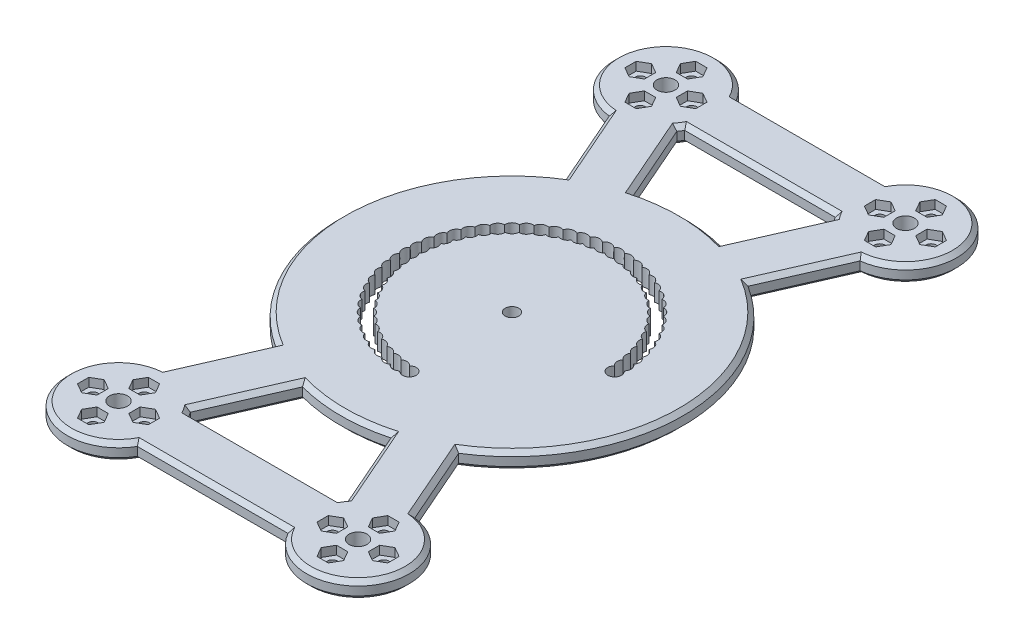
SolidWorks part; units mm, degrees
ref_plane "Front Plane" through (0, 0, 0) normal (0, 0, 1) x (1, 0, 0)
ref_plane "Top Plane" through (0, 0, 0) normal (0, 1, 0) x (1, 0, 0)
ref_plane "Right Plane" through (0, 0, 0) normal (1, 0, 0) x (0, 0, -1)
sketch "Sketch1" plane through (0, 0, 0) normal (0, 1, 0) x (1, 0, 0)
  line L1 (-50, -95) -> (50, -95)
  line L2 (-50, -95) -> (-50, 95)
  line L3 (-50, 95) -> (50, 95)
  line L4 (50, -95) -> (50, 95)
  line L5 (-50, -95) -> (50, 95) construction
  line L6 (-50, 95) -> (50, -95) construction
  point P0 (0, 0)
  dimension "D1" = 100
  dimension "D2" = 190
extrude "Boss-Extrude1" add sketch "Sketch1" along normal blind 5
sketch "Sketch2" plane through (0, 5, 0) normal (0, 1, 0) x (1, 0, 0)
  line L0 (0, 95) -> (0, -95) construction
  line L1 (50, 95) -> (-50, 95) construction
  line L2 (-50, -95) -> (50, -95) construction
  line L3 (-50, 0) -> (50, 0) construction
  line L4 (-50, 95) -> (-50, -95) construction
  line L5 (50, -95) -> (50, 95) construction
  line L6 (0, 0) -> (50, 0) construction
  line L7 (0, 0) -> (30, 0) construction
  circle A0 centre (0, 0) radius 2
  arc A1 (30, 0) -> (0, 30) centre (0, 0) ccw construction
  arc A31 (28.5755, 1.4038) -> (31.2801, 1.5367) centre (30, 0) ccw
  arc A33 (31.2801, 1.5367) -> (30.9788, 4.5953) centre (29.8555, 2.9405) ccw
  arc A34 (30.9788, 4.5953) -> (30.3792, 7.6096) centre (29.4236, 5.8527) ccw
  arc A35 (30.3792, 7.6096) -> (29.4871, 10.5506) centre (28.7082, 8.7085) ccw
  arc A36 (29.4871, 10.5506) -> (28.311, 13.3901) centre (27.7164, 11.4805) ccw
  arc A37 (28.311, 13.3901) -> (26.8622, 16.1006) centre (26.4576, 14.1419) ccw
  arc A38 (26.8622, 16.1006) -> (25.1547, 18.656) centre (24.9441, 16.6671) ccw
  arc A39 (25.1547, 18.656) -> (23.205, 21.0317) centre (23.1903, 19.0318) ccw
  arc A40 (23.205, 21.0317) -> (21.0317, 23.205) centre (21.2132, 21.2132) ccw
  arc A41 (21.0317, 23.205) -> (18.656, 25.1547) centre (19.0318, 23.1903) ccw
  arc A42 (18.656, 25.1547) -> (16.1006, 26.8622) centre (16.6671, 24.9441) ccw
  arc A43 (16.1006, 26.8622) -> (13.3901, 28.311) centre (14.1419, 26.4576) ccw
  arc A44 (13.3901, 28.311) -> (10.5506, 29.4871) centre (11.4805, 27.7164) ccw
  arc A45 (10.5506, 29.4871) -> (7.6096, 30.3792) centre (8.7085, 28.7082) ccw
  arc A46 (7.6096, 30.3792) -> (4.5953, 30.9788) centre (5.8527, 29.4236) ccw
  arc A47 (1.4038, 28.5755) -> (4.1979, 28.3003) centre (2.9405, 29.8555) ccw
  arc A48 (-1.4038, 28.5755) -> (1.4038, 28.5755) centre (0, 30) ccw
  arc A49 (-4.1979, 28.3003) -> (-1.4038, 28.5755) centre (-2.9405, 29.8555) ccw
  arc A50 (-6.9516, 27.7525) -> (-4.1979, 28.3003) centre (-5.8527, 29.4236) ccw
  arc A51 (-9.6384, 26.9375) -> (-6.9516, 27.7525) centre (-8.7085, 28.7082) ccw
  arc A52 (-12.2323, 25.8631) -> (-9.6384, 26.9375) centre (-11.4805, 27.7164) ccw
  arc A53 (-14.7084, 24.5396) -> (-12.2323, 25.8631) centre (-14.1419, 26.4576) ccw
  arc A54 (-17.0429, 22.9797) -> (-14.7084, 24.5396) centre (-16.6671, 24.9441) ccw
  arc A55 (-19.2133, 21.1986) -> (-17.0429, 22.9797) centre (-19.0318, 23.1903) ccw
  arc A56 (-21.1986, 19.2133) -> (-19.2133, 21.1986) centre (-21.2132, 21.2132) ccw
  arc A57 (-22.9797, 17.0429) -> (-21.1986, 19.2133) centre (-23.1903, 19.0318) ccw
  arc A58 (-24.5396, 14.7084) -> (-22.9797, 17.0429) centre (-24.9441, 16.6671) ccw
  arc A59 (-25.8631, 12.2323) -> (-24.5396, 14.7084) centre (-26.4576, 14.1419) ccw
  arc A60 (-26.9375, 9.6384) -> (-25.8631, 12.2323) centre (-27.7164, 11.4805) ccw
  arc A61 (-29.4871, 10.5506) -> (-30.3792, 7.6096) centre (-28.7082, 8.7085) ccw
  arc A62 (-28.3003, 4.1979) -> (-27.7525, 6.9516) centre (-29.4236, 5.8527) ccw
  arc A63 (-28.5755, 1.4038) -> (-28.3003, 4.1979) centre (-29.8555, 2.9405) ccw
  arc A64 (-28.5755, -1.4038) -> (-28.5755, 1.4038) centre (-30, 0) ccw
  arc A65 (-28.3003, -4.1979) -> (-28.5755, -1.4038) centre (-29.8555, -2.9405) ccw
  arc A66 (-27.7525, -6.9516) -> (-28.3003, -4.1979) centre (-29.4236, -5.8527) ccw
  arc A67 (-26.9375, -9.6384) -> (-27.7525, -6.9516) centre (-28.7082, -8.7085) ccw
  arc A68 (-25.8631, -12.2323) -> (-26.9375, -9.6384) centre (-27.7164, -11.4805) ccw
  arc A69 (-24.5396, -14.7084) -> (-25.8631, -12.2323) centre (-26.4576, -14.1419) ccw
  arc A70 (-22.9797, -17.0429) -> (-24.5396, -14.7084) centre (-24.9441, -16.6671) ccw
  arc A71 (-21.1986, -19.2133) -> (-22.9797, -17.0429) centre (-23.1903, -19.0318) ccw
  arc A72 (-19.2133, -21.1986) -> (-21.1986, -19.2133) centre (-21.2132, -21.2132) ccw
  arc A73 (-17.0429, -22.9797) -> (-19.2133, -21.1986) centre (-19.0318, -23.1903) ccw
  arc A74 (-14.7084, -24.5396) -> (-17.0429, -22.9797) centre (-16.6671, -24.9441) ccw
  arc A75 (-12.2323, -25.8631) -> (-14.7084, -24.5396) centre (-14.1419, -26.4576) ccw
  arc A76 (-9.6384, -26.9375) -> (-12.2323, -25.8631) centre (-11.4805, -27.7164) ccw
  arc A77 (-6.9516, -27.7525) -> (-9.6384, -26.9375) centre (-8.7085, -28.7082) ccw
  arc A78 (-4.1979, -28.3003) -> (-6.9516, -27.7525) centre (-5.8527, -29.4236) ccw
  arc A79 (-1.4038, -28.5755) -> (-4.1979, -28.3003) centre (-2.9405, -29.8555) ccw
  arc A80 (-1.5367, -31.2801) -> (-1.4038, -28.5755) centre (0, -30) ccw
  arc A81 (-4.5953, -30.9788) -> (-1.5367, -31.2801) centre (-2.9405, -29.8555) ccw
  arc A82 (-7.6096, -30.3792) -> (-4.5953, -30.9788) centre (-5.8527, -29.4236) ccw
  arc A83 (-10.5506, -29.4871) -> (-7.6096, -30.3792) centre (-8.7085, -28.7082) ccw
  arc A84 (-13.3901, -28.311) -> (-10.5506, -29.4871) centre (-11.4805, -27.7164) ccw
  arc A85 (-16.1006, -26.8622) -> (-13.3901, -28.311) centre (-14.1419, -26.4576) ccw
  arc A86 (-18.656, -25.1547) -> (-16.1006, -26.8622) centre (-16.6671, -24.9441) ccw
  arc A87 (-21.0317, -23.205) -> (-18.656, -25.1547) centre (-19.0318, -23.1903) ccw
  arc A88 (-23.205, -21.0317) -> (-21.0317, -23.205) centre (-21.2132, -21.2132) ccw
  arc A89 (-25.1547, -18.656) -> (-23.205, -21.0317) centre (-23.1903, -19.0318) ccw
  arc A90 (-26.8622, -16.1006) -> (-25.1547, -18.656) centre (-24.9441, -16.6671) ccw
  arc A91 (-28.311, -13.3901) -> (-26.8622, -16.1006) centre (-26.4576, -14.1419) ccw
  arc A92 (-29.4871, -10.5506) -> (-28.311, -13.3901) centre (-27.7164, -11.4805) ccw
  arc A93 (-30.3792, -7.6096) -> (-29.4871, -10.5506) centre (-28.7082, -8.7085) ccw
  arc A94 (-30.9788, -4.5953) -> (-30.3792, -7.6096) centre (-29.4236, -5.8527) ccw
  arc A95 (-31.2801, -1.5367) -> (-30.9788, -4.5953) centre (-29.8555, -2.9405) ccw
  arc A96 (-31.2801, 1.5367) -> (-31.2801, -1.5367) centre (-30, 0) ccw
  arc A97 (-30.9788, 4.5953) -> (-31.2801, 1.5367) centre (-29.8555, 2.9405) ccw
  arc A98 (-30.3792, 7.6096) -> (-30.9788, 4.5953) centre (-29.4236, 5.8527) ccw
  arc A99 (-27.7525, 6.9516) -> (-26.9375, 9.6384) centre (-28.7082, 8.7085) ccw
  arc A100 (-28.311, 13.3901) -> (-29.4871, 10.5506) centre (-27.7164, 11.4805) ccw
  arc A101 (-26.8622, 16.1006) -> (-28.311, 13.3901) centre (-26.4576, 14.1419) ccw
  arc A102 (-25.1547, 18.656) -> (-26.8622, 16.1006) centre (-24.9441, 16.6671) ccw
  arc A103 (-23.205, 21.0317) -> (-25.1547, 18.656) centre (-23.1903, 19.0318) ccw
  arc A104 (-21.0317, 23.205) -> (-23.205, 21.0317) centre (-21.2132, 21.2132) ccw
  arc A105 (-18.656, 25.1547) -> (-21.0317, 23.205) centre (-19.0318, 23.1903) ccw
  arc A106 (-16.1006, 26.8622) -> (-18.656, 25.1547) centre (-16.6671, 24.9441) ccw
  arc A107 (-13.3901, 28.311) -> (-16.1006, 26.8622) centre (-14.1419, 26.4576) ccw
  arc A108 (28.3003, 4.1979) -> (28.5755, 1.4038) centre (29.8555, 2.9405) ccw
  arc A109 (27.7525, 6.9516) -> (28.3003, 4.1979) centre (29.4236, 5.8527) ccw
  arc A110 (26.9375, 9.6384) -> (27.7525, 6.9516) centre (28.7082, 8.7085) ccw
  arc A111 (25.8631, 12.2323) -> (26.9375, 9.6384) centre (27.7164, 11.4805) ccw
  arc A112 (24.5396, 14.7084) -> (25.8631, 12.2323) centre (26.4576, 14.1419) ccw
  arc A113 (22.9797, 17.0429) -> (24.5396, 14.7084) centre (24.9441, 16.6671) ccw
  arc A114 (21.1986, 19.2133) -> (22.9797, 17.0429) centre (23.1903, 19.0318) ccw
  arc A115 (19.2133, 21.1986) -> (21.1986, 19.2133) centre (21.2132, 21.2132) ccw
  arc A116 (17.0429, 22.9797) -> (19.2133, 21.1986) centre (19.0318, 23.1903) ccw
  arc A117 (-10.5506, 29.4871) -> (-13.3901, 28.311) centre (-11.4805, 27.7164) ccw
  arc A118 (14.7084, 24.5396) -> (17.0429, 22.9797) centre (16.6671, 24.9441) ccw
  arc A119 (-7.6096, 30.3792) -> (-10.5506, 29.4871) centre (-8.7085, 28.7082) ccw
  arc A120 (12.2323, 25.8631) -> (14.7084, 24.5396) centre (14.1419, 26.4576) ccw
  arc A121 (-4.5953, 30.9788) -> (-7.6096, 30.3792) centre (-5.8527, 29.4236) ccw
  arc A122 (-1.5367, 31.2801) -> (-4.5953, 30.9788) centre (-2.9405, 29.8555) ccw
  arc A123 (9.6384, 26.9375) -> (12.2323, 25.8631) centre (11.4805, 27.7164) ccw
  arc A124 (6.9516, 27.7525) -> (9.6384, 26.9375) centre (8.7085, 28.7082) ccw
  arc A125 (1.5367, 31.2801) -> (-1.5367, 31.2801) centre (0, 30) ccw
  arc A126 (4.5953, 30.9788) -> (1.5367, 31.2801) centre (2.9405, 29.8555) ccw
  arc A127 (4.1979, 28.3003) -> (6.9516, 27.7525) centre (5.8527, 29.4236) ccw
  dimension "D2" = 4
  dimension "D3" = 30
  dimension "D1" = 0
  dimension "D5" = 30
  dimension "D4" = 49
extrude "Cut-Extrude1" cut sketch "Sketch2" against normal through all
sketch "Sketch3" plane through (0, 5, 0) normal (0, 1, 0) x (1, 0, 0)
  line L0 (-35, 80) -> (-35, 87.5) construction
  line L1 (0, 0) -> (0, -95) construction
  line L2 (50, 95) -> (-50, 95) construction
  line L3 (-50, -95) -> (50, -95) construction
  line L4 (-50, 0) -> (50, 0) construction
  line L5 (-50, 95) -> (-50, -95) construction
  line L6 (50, -95) -> (50, 95) construction
  line L19 (0, 0) -> (0, 95) construction
  line L29 (0, 0) -> (-35, 80) construction
  line L30 (-22.922, 71.1049) -> (-12.943, 48.2957)
  line L31 (-36.6644, 65.0926) -> (-26.6854, 42.2835)
  line L32 (22.922, 71.1049) -> (12.943, 48.2957)
  line L33 (0, 0) -> (35, 80) construction
  line L34 (36.6644, 65.0926) -> (26.6854, 42.2835)
  line L35 (-36.6644, -65.0926) -> (-26.6854, -42.2835)
  line L36 (0, 0) -> (-35, -80) construction
  line L37 (-22.922, -71.1049) -> (-12.943, -48.2957)
  line L38 (22.922, -71.1049) -> (12.943, -48.2957)
  line L39 (0, 0) -> (35, -80) construction
  line L40 (36.6644, -65.0926) -> (26.6854, -42.2835)
  line L41 (-35, 80) -> (35, 80) construction
  line L42 (-22.0096, 87.5) -> (22.0096, 87.5)
  line L43 (-22.0096, 72.5) -> (22.0096, 72.5)
  line L44 (-22.0096, -87.5) -> (22.0096, -87.5)
  line L45 (-35, -80) -> (35, -80) construction
  line L46 (-22.0096, -72.5) -> (22.0096, -72.5)
  circle A1 centre (-35, 80) radius 2.625
  circle A2 centre (-35, 87.5) radius 1.5
  circle A3 centre (-27.5, 80) radius 1.5
  circle A4 centre (-35, 72.5) radius 1.5
  circle A5 centre (-42.5, 80) radius 1.5
  circle A6 centre (-35, 80) radius 7.5 construction
  circle A7 centre (35, 72.5) radius 1.5
  circle A8 centre (42.5, 80) radius 1.5
  circle A9 centre (27.5, 80) radius 1.5
  circle A10 centre (35, 87.5) radius 1.5
  circle A11 centre (35, 80) radius 2.625
  circle A12 centre (-35, -72.5) radius 1.5
  circle A13 centre (-42.5, -80) radius 1.5
  circle A14 centre (-35, -80) radius 2.625
  circle A15 centre (-35, -87.5) radius 1.5
  circle A16 centre (-27.5, -80) radius 1.5
  circle A17 centre (27.5, -80) radius 1.5
  circle A18 centre (35, -87.5) radius 1.5
  circle A19 centre (42.5, -80) radius 1.5
  circle A20 centre (35, -80) radius 2.625
  circle A21 centre (35, -72.5) radius 1.5
  arc A30 (12.943, 48.2957) -> (-12.943, 48.2957) centre (0, 0) ccw
  arc A31 (-22.922, 71.1049) -> (-22.0096, 72.5) centre (-35, 80) ccw
  arc A32 (22.922, 71.1049) -> (22.0096, 72.5) centre (35, 80) cw
  arc A33 (-22.922, -71.1049) -> (-22.0096, -72.5) centre (-35, -80) cw
  arc A34 (22.922, -71.1049) -> (22.0096, -72.5) centre (35, -80) ccw
  arc A35 (-26.6854, 42.2835) -> (-26.6854, -42.2835) centre (0, 0) ccw
  arc A36 (-12.943, -48.2957) -> (12.943, -48.2957) centre (0, 0) ccw
  arc A37 (26.6854, -42.2835) -> (26.6854, 42.2835) centre (0, 0) ccw
  arc A38 (-22.0096, -87.5) -> (-36.6644, -65.0926) centre (-35, -80) cw
  arc A39 (22.0096, -87.5) -> (36.6644, -65.0926) centre (35, -80) ccw
  arc A40 (22.0096, 87.5) -> (36.6644, 65.0926) centre (35, 80) cw
  arc A41 (-22.0096, 87.5) -> (-36.6644, 65.0926) centre (-35, 80) ccw
  dimension "D1" = 5.25
  dimension "D4" = 3
  dimension "D7" = 15
  dimension "D2" = 15
  dimension "D3" = 15
  dimension "D6" = 7.5
  dimension "D8" = 15
  dimension "D5" = 4
extrude "Cut-Extrude2" cut sketch "Sketch3" against normal through all flip side to cut
sketch "Sketch4" plane through (0, 5, 0) normal (0, 1, 0) x (1, 0, 0)
  line L0 (0, 98.7891) -> (0, -99.9401) construction
  line L1 (-39.65, 81.6454) -> (-42.5, 83.2909)
  line L2 (-42.5, 83.2909) -> (-45.35, 81.6454)
  line L3 (-45.35, 81.6454) -> (-45.35, 78.3546)
  line L4 (-45.35, 78.3546) -> (-42.5, 76.7091)
  line L5 (-42.5, 76.7091) -> (-39.65, 78.3546)
  line L6 (-39.65, 78.3546) -> (-39.65, 81.6454)
  line L7 (-31.7091, 72.5) -> (-33.3546, 75.35)
  line L8 (-33.3546, 75.35) -> (-36.6454, 75.35)
  line L9 (-36.6454, 75.35) -> (-38.2909, 72.5)
  line L10 (-38.2909, 72.5) -> (-36.6454, 69.65)
  line L11 (-36.6454, 69.65) -> (-33.3546, 69.65)
  line L12 (-33.3546, 69.65) -> (-31.7091, 72.5)
  line L13 (-24.65, 81.6454) -> (-27.5, 83.2909)
  line L14 (-27.5, 83.2909) -> (-30.35, 81.6454)
  line L15 (-30.35, 81.6454) -> (-30.35, 78.3546)
  line L16 (-30.35, 78.3546) -> (-27.5, 76.7091)
  line L17 (-27.5, 76.7091) -> (-24.65, 78.3546)
  line L18 (-24.65, 78.3546) -> (-24.65, 81.6454)
  line L19 (-31.7091, 87.5) -> (-33.3546, 90.35)
  line L20 (-33.3546, 90.35) -> (-36.6454, 90.35)
  line L21 (-36.6454, 90.35) -> (-38.2909, 87.5)
  line L22 (-38.2909, 87.5) -> (-36.6454, 84.65)
  line L23 (-36.6454, 84.65) -> (-33.3546, 84.65)
  line L24 (-33.3546, 84.65) -> (-31.7091, 87.5)
  line L25 (-62.5794, 0) -> (65.9448, 0) construction
  line L26 (33.3546, 69.65) -> (31.7091, 72.5)
  line L27 (36.6454, 69.65) -> (33.3546, 69.65)
  line L28 (38.2909, 72.5) -> (36.6454, 69.65)
  line L29 (36.6454, 75.35) -> (38.2909, 72.5)
  line L30 (33.3546, 75.35) -> (36.6454, 75.35)
  line L31 (31.7091, 72.5) -> (33.3546, 75.35)
  line L32 (39.65, 78.3546) -> (39.65, 81.6454)
  line L33 (42.5, 76.7091) -> (39.65, 78.3546)
  line L34 (45.35, 78.3546) -> (42.5, 76.7091)
  line L35 (45.35, 81.6454) -> (45.35, 78.3546)
  line L36 (42.5, 83.2909) -> (45.35, 81.6454)
  line L37 (39.65, 81.6454) -> (42.5, 83.2909)
  line L38 (33.3546, 84.65) -> (31.7091, 87.5)
  line L39 (36.6454, 84.65) -> (33.3546, 84.65)
  line L40 (38.2909, 87.5) -> (36.6454, 84.65)
  line L41 (36.6454, 90.35) -> (38.2909, 87.5)
  line L42 (33.3546, 90.35) -> (36.6454, 90.35)
  line L43 (31.7091, 87.5) -> (33.3546, 90.35)
  line L44 (24.65, 78.3546) -> (24.65, 81.6454)
  line L45 (27.5, 76.7091) -> (24.65, 78.3546)
  line L46 (30.35, 78.3546) -> (27.5, 76.7091)
  line L47 (30.35, 81.6454) -> (30.35, 78.3546)
  line L48 (27.5, 83.2909) -> (30.35, 81.6454)
  line L49 (24.65, 81.6454) -> (27.5, 83.2909)
  line L50 (36.6454, -84.65) -> (33.3546, -84.65)
  line L51 (38.2909, -87.5) -> (36.6454, -84.65)
  line L52 (36.6454, -90.35) -> (38.2909, -87.5)
  line L53 (33.3546, -90.35) -> (36.6454, -90.35)
  line L54 (31.7091, -87.5) -> (33.3546, -90.35)
  line L55 (33.3546, -84.65) -> (31.7091, -87.5)
  line L56 (42.5, -76.7091) -> (39.65, -78.3546)
  line L57 (45.35, -78.3546) -> (42.5, -76.7091)
  line L58 (45.35, -81.6454) -> (45.35, -78.3546)
  line L59 (42.5, -83.2909) -> (45.35, -81.6454)
  line L60 (39.65, -81.6454) -> (42.5, -83.2909)
  line L61 (39.65, -78.3546) -> (39.65, -81.6454)
  line L62 (36.6454, -69.65) -> (33.3546, -69.65)
  line L63 (38.2909, -72.5) -> (36.6454, -69.65)
  line L64 (36.6454, -75.35) -> (38.2909, -72.5)
  line L65 (33.3546, -75.35) -> (36.6454, -75.35)
  line L66 (31.7091, -72.5) -> (33.3546, -75.35)
  line L67 (33.3546, -69.65) -> (31.7091, -72.5)
  line L68 (27.5, -76.7091) -> (24.65, -78.3546)
  line L69 (30.35, -78.3546) -> (27.5, -76.7091)
  line L70 (30.35, -81.6454) -> (30.35, -78.3546)
  line L71 (27.5, -83.2909) -> (30.35, -81.6454)
  line L72 (24.65, -81.6454) -> (27.5, -83.2909)
  line L73 (24.65, -78.3546) -> (24.65, -81.6454)
  line L74 (-33.3546, -69.65) -> (-31.7091, -72.5)
  line L75 (-36.6454, -69.65) -> (-33.3546, -69.65)
  line L76 (-38.2909, -72.5) -> (-36.6454, -69.65)
  line L77 (-36.6454, -75.35) -> (-38.2909, -72.5)
  line L78 (-33.3546, -75.35) -> (-36.6454, -75.35)
  line L79 (-31.7091, -72.5) -> (-33.3546, -75.35)
  line L80 (-39.65, -78.3546) -> (-39.65, -81.6454)
  line L81 (-42.5, -76.7091) -> (-39.65, -78.3546)
  line L82 (-45.35, -78.3546) -> (-42.5, -76.7091)
  line L83 (-45.35, -81.6454) -> (-45.35, -78.3546)
  line L84 (-42.5, -83.2909) -> (-45.35, -81.6454)
  line L85 (-39.65, -81.6454) -> (-42.5, -83.2909)
  line L86 (-33.3546, -84.65) -> (-31.7091, -87.5)
  line L87 (-36.6454, -84.65) -> (-33.3546, -84.65)
  line L88 (-38.2909, -87.5) -> (-36.6454, -84.65)
  line L89 (-36.6454, -90.35) -> (-38.2909, -87.5)
  line L90 (-33.3546, -90.35) -> (-36.6454, -90.35)
  line L91 (-31.7091, -87.5) -> (-33.3546, -90.35)
  line L92 (-24.65, -78.3546) -> (-24.65, -81.6454)
  line L93 (-27.5, -76.7091) -> (-24.65, -78.3546)
  line L94 (-30.35, -78.3546) -> (-27.5, -76.7091)
  line L95 (-30.35, -81.6454) -> (-30.35, -78.3546)
  line L96 (-27.5, -83.2909) -> (-30.35, -81.6454)
  line L97 (-24.65, -81.6454) -> (-27.5, -83.2909)
  circle A0 centre (-42.5, 80) radius 2.85 construction
  circle A1 centre (-35, 72.5) radius 2.85 construction
  circle A2 centre (-27.5, 80) radius 2.85 construction
  circle A3 centre (-35, 87.5) radius 2.85 construction
  point P28 (-45.35, 80)
  dimension "D1" = 5.7
  dimension "D2" = 5.7
  dimension "D3" = 5.7
  dimension "D4" = 5.7
extrude "Cut-Extrude3" cut sketch "Sketch4" against normal blind 2.5
chamfer "Chamfer1" distance 1.25 angle 45 48 edges at (0, 0, -72.5) (22.4464, 0, -71.7898) (17.9325, 0, -59.7003) (0, 0, -50) (-17.9325, 0, -59.7003) (-22.4464, 0, -71.7898) (-17.9325, 0, 59.7003) (0, 0, 50) (17.9325, 0, 59.7003) (22.4464, 0, 71.7898) (0, 0, 72.5) (-22.4464, 0, 71.7898) (0, 0, -87.5) (-47.5536, 0, -88.2102) (-31.6749, 0, -53.688) (-50, 0, 0) (-31.6749, 0, 53.688) (-47.5536, 0, 88.2102) (0, 0, 87.5) (47.5536, 0, 88.2102) (31.6749, 0, 53.688) (50, 0, 0) (31.6749, 0, -53.688) (47.5536, 0, -88.2102) (0, 5, -50) (17.9325, 5, -59.7003) (22.4464, 5, -71.7898) (0, 5, -72.5) (-22.4464, 5, -71.7898) (-17.9325, 5, -59.7003) (31.6749, 5, -53.688) (50, 5, 0) (31.6749, 5, 53.688) (47.5536, 5, 88.2102) (0, 5, 87.5) (-47.5536, 5, 88.2102) (-31.6749, 5, 53.688) (-50, 5, 0) (-31.6749, 5, -53.688) (-47.5536, 5, -88.2102) (0, 5, -87.5) (47.5536, 5, -88.2102) (22.4464, 5, 71.7898) (17.9325, 5, 59.7003) (0, 5, 50) (-17.9325, 5, 59.7003) (-22.4464, 5, 71.7898) (0, 5, 72.5)
